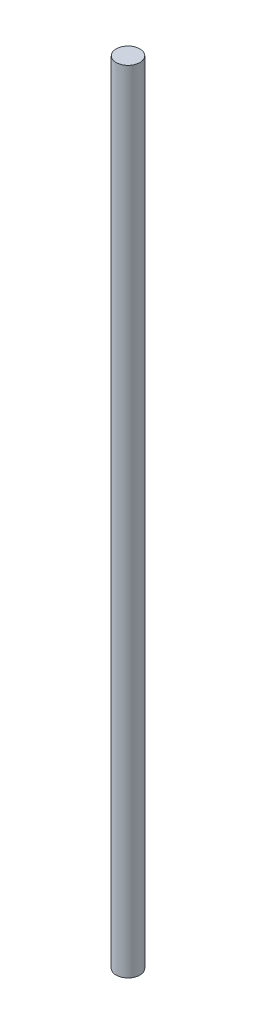
SolidWorks part; units mm, degrees
other "Frame Tie Stud Left"
ref_plane "Front Plane" through (0, 0, 0) normal (0, 0, 1) x (1, 0, 0)
ref_plane "Top Plane" through (0, 0, 0) normal (0, 1, 0) x (1, 0, 0)
ref_plane "Right Plane" through (0, 0, 0) normal (1, 0, 0) x (0, 0, -1)
sketch3d "Base Outline Sketch datum points"
  point P0 (0, 65.1, 0)
  point P1 (10, 65.1, 0)
  point P2 (0, 65.1, -10)
ref_plane "Base Outline Sketch plane" through (0, 65.1, 0) normal (0, 1, 0) x (1, 0, 0)
sketch "Base Outline Sketch" plane through (0, 65.1, 0) normal (0, 1, 0) x (1, 0, 0)
  circle A0 centre (-56.2917, -50) radius 1.5
extrude "Base Outline" add sketch "Base Outline Sketch" along normal blind 100 separate body
